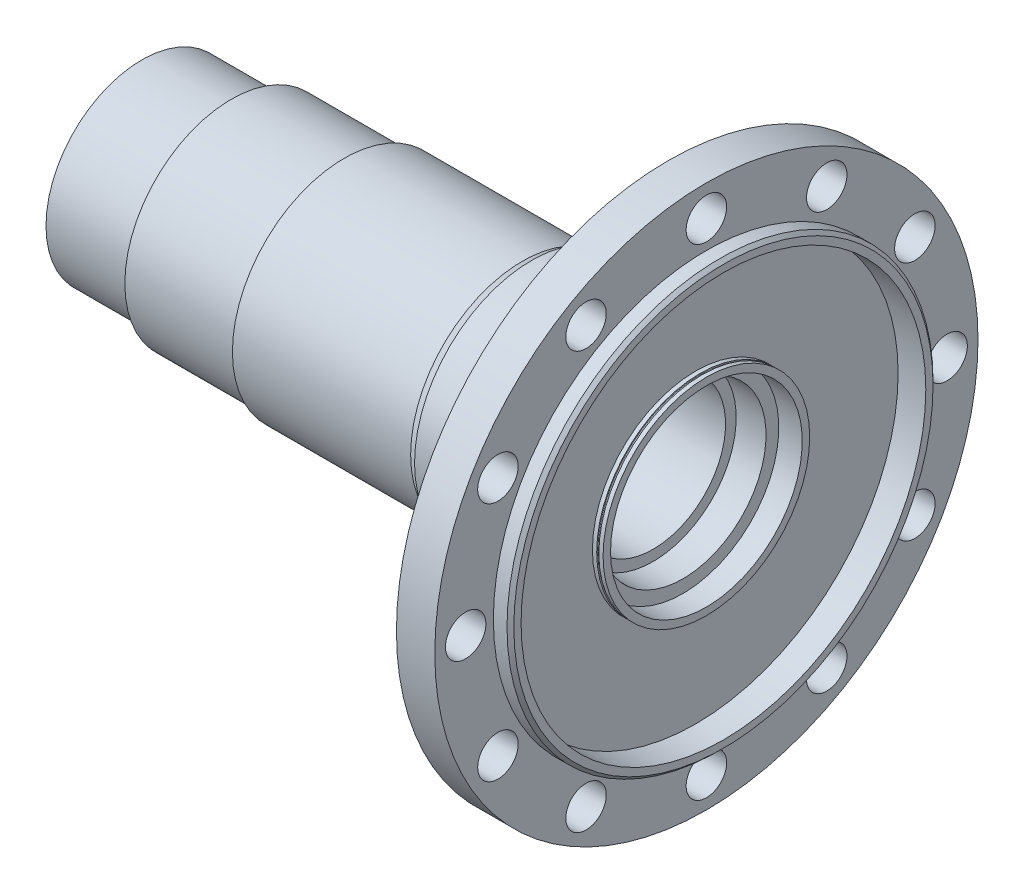
SolidWorks part; units mm, degrees
ref_plane "Спереди" through (0, 0, 0) normal (0, 0, 1) x (1, 0, 0)
ref_plane "Сверху" through (0, 0, 0) normal (0, 1, 0) x (1, 0, 0)
ref_plane "Справа" through (0, 0, 0) normal (1, 0, 0) x (0, 0, -1)
sketch "Эскиз1" plane through (0, 0, 0) normal (0, 0, 1) x (1, 0, 0)
  line L0 (0, 0) -> (273, 0)
  line L1 (0, 0) -> (0, 45)
  line L2 (0, 45) -> (42, 45)
  line L3 (42, 45) -> (42, 50)
  line L4 (42, 50) -> (95, 50)
  line L5 (95, 50) -> (95, 52.5)
  line L6 (95, 52.5) -> (178.6699, 52.5)
  line L7 (178.6699, 52.5) -> (183, 55)
  line L8 (183, 55) -> (215, 55)
  line L9 (215, 55) -> (215, 62.5)
  line L10 (215, 62.5) -> (239, 62.5)
  line L11 (239, 62.5) -> (239, 100)
  line L12 (239, 100) -> (247, 100)
  line L13 (247, 100) -> (247, 127.5)
  line L14 (247, 127.5) -> (265, 127.5)
  line L15 (265, 127.5) -> (265, 100)
  line L16 (265, 100) -> (271.4, 100)
  line L17 (271.4, 100) -> (273, 98.4)
  line L18 (273, 98.4) -> (273, 0)
revolve "Повернуть1" add sketch "Эскиз1" angle 360 about L0
sketch "Эскиз2" plane through (0, 0, 0) normal (0, 0, 1) x (1, 0, 0)
  line L0 (0, 0) -> (273, 0)
  line L1 (0, 0) -> (0, 31)
  line L2 (0, 31) -> (203.5, 31)
  line L3 (203.5, 31) -> (203.5, 34)
  line L4 (203.5, 34) -> (240, 34)
  line L5 (240, 34) -> (240, 39)
  line L6 (240, 39) -> (254, 39)
  line L7 (254, 39) -> (254, 45)
  line L8 (254, 45) -> (265, 45)
  line L9 (265, 45) -> (265, 95)
  line L10 (265, 95) -> (273, 95)
  line L11 (273, 95) -> (273, 0)
revolve "Вырез-Повернуть1" cut sketch "Эскиз2" angle 360 about L0
sketch "Эскиз3" plane through (0, 0, 0) normal (0, 0, 1) x (1, 0, 0)
  line L0 (0, 0) -> (273, 0) construction
  line L1 (260, 48.5) -> (262, 48.5)
  line L2 (262, 48.5) -> (262, 95)
  line L3 (262, 95) -> (260, 95)
  line L4 (260, 95) -> (260, 48.5)
revolve "Rear_recess_left" cut sketch "Эскиз3" angle 360 about L0
sketch "Эскиз4" plane through (0, 0, 0) normal (0, 0, 1) x (1, 0, 0)
  line L0 (0, 0) -> (273, 0) construction
  line L1 (263, 48) -> (263, 95)
  line L2 (263, 95) -> (262, 95)
  line L3 (262, 95) -> (262, 48)
  arc A0 (262, 48) -> (262.5, 47.5) centre (262.5, 48) ccw
  arc A1 (262.5, 47.5) -> (263, 48) centre (262.5, 48) ccw
revolve "Collar_groove_nominal" cut sketch "Эскиз4" angle 360 about L0
sketch "Эскиз5" plane through (0, 0, 0) normal (0, 0, 1) x (1, 0, 0)
  line L0 (0, 0) -> (273, 0) construction
  line L1 (263, 48.5) -> (265, 48.5)
  line L2 (265, 48.5) -> (265, 95)
  line L3 (265, 95) -> (263, 95)
  line L4 (263, 95) -> (263, 48.5)
revolve "Rear_recess_lip" cut sketch "Эскиз5" angle 360 about L0
sketch "Эскиз6" plane through (0, 0, 0) normal (1, 0, 0) x (0, 0, -1)
  circle A0 centre (0, 113) radius 9.5
extrude "Вырез-Вытянуть1" cut sketch "Эскиз6" along normal through all
sketch "Эскиз7" plane through (0, 0, 0) normal (1, 0, 0) x (0, 0, -1)
  circle A0 centre (-56.5, 97.8609) radius 9.5
extrude "Вырез-Вытянуть2" cut sketch "Эскиз7" along normal through all
sketch "Эскиз8" plane through (0, 0, 0) normal (1, 0, 0) x (0, 0, -1)
  circle A0 centre (-97.8609, 56.5) radius 9.5
extrude "Вырез-Вытянуть3" cut sketch "Эскиз8" along normal through all
sketch "Эскиз9" plane through (0, 0, 0) normal (1, 0, 0) x (0, 0, -1)
  circle A0 centre (-113, 0) radius 9.5
extrude "Вырез-Вытянуть4" cut sketch "Эскиз9" along normal through all
sketch "Эскиз10" plane through (0, 0, 0) normal (1, 0, 0) x (0, 0, -1)
  circle A0 centre (-97.8609, -56.5) radius 9.5
extrude "Вырез-Вытянуть5" cut sketch "Эскиз10" along normal through all
sketch "Эскиз11" plane through (0, 0, 0) normal (1, 0, 0) x (0, 0, -1)
  circle A0 centre (-56.5, -97.8609) radius 9.5
extrude "Вырез-Вытянуть6" cut sketch "Эскиз11" along normal through all
sketch "Эскиз12" plane through (0, 0, 0) normal (1, 0, 0) x (0, 0, -1)
  circle A0 centre (0, -113) radius 9.5
extrude "Вырез-Вытянуть7" cut sketch "Эскиз12" along normal through all
sketch "Эскиз13" plane through (0, 0, 0) normal (1, 0, 0) x (0, 0, -1)
  circle A0 centre (56.5, -97.8609) radius 9.5
extrude "Вырез-Вытянуть8" cut sketch "Эскиз13" along normal through all
sketch "Эскиз14" plane through (0, 0, 0) normal (1, 0, 0) x (0, 0, -1)
  circle A0 centre (97.8609, -56.5) radius 9.5
extrude "Вырез-Вытянуть9" cut sketch "Эскиз14" along normal through all
sketch "Эскиз15" plane through (0, 0, 0) normal (1, 0, 0) x (0, 0, -1)
  circle A0 centre (113, 0) radius 9.5
extrude "Вырез-Вытянуть10" cut sketch "Эскиз15" along normal through all
sketch "Эскиз16" plane through (0, 0, 0) normal (1, 0, 0) x (0, 0, -1)
  circle A0 centre (97.8609, 56.5) radius 9.5
extrude "Вырез-Вытянуть11" cut sketch "Эскиз16" along normal through all
sketch "Эскиз17" plane through (0, 0, 0) normal (1, 0, 0) x (0, 0, -1)
  circle A0 centre (56.5, 97.8609) radius 9.5
extrude "Вырез-Вытянуть12" cut sketch "Эскиз17" along normal through all
